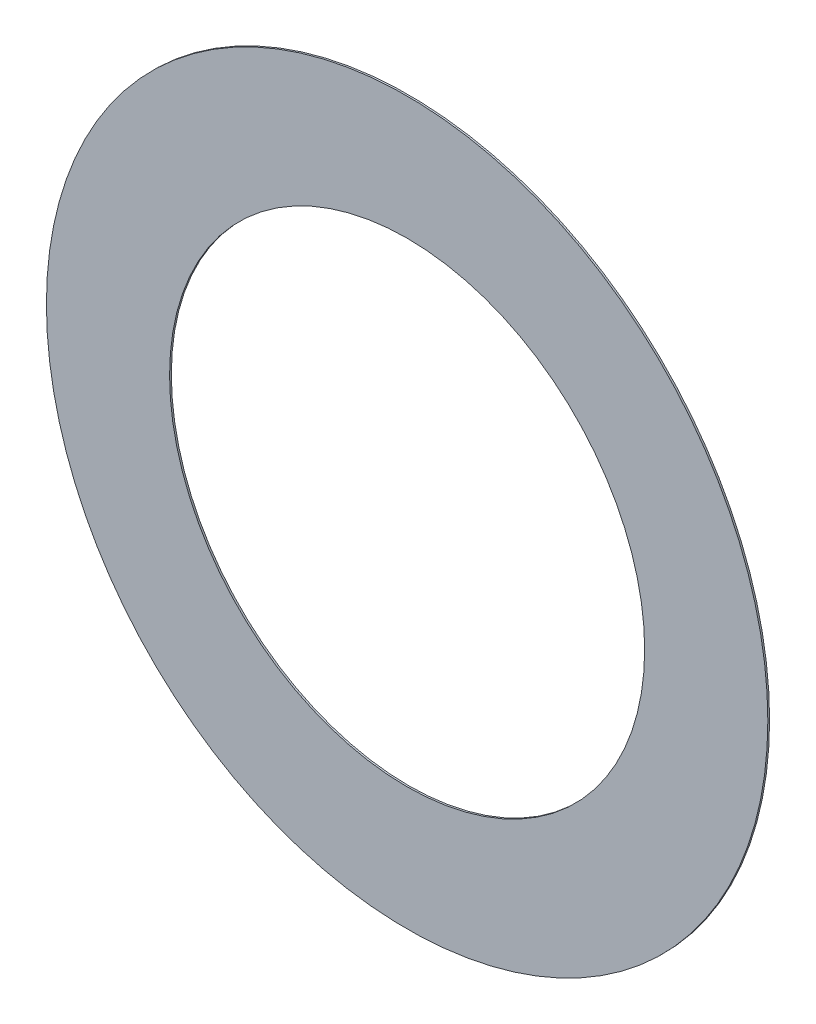
SolidWorks part; units mm, degrees
ref_plane "Front Plane" through (0, 0, 0) normal (0, 0, 1) x (1, 0, 0)
ref_plane "Top Plane" through (0, 0, 0) normal (0, 1, 0) x (1, 0, 0)
ref_plane "Right Plane" through (0, 0, 0) normal (1, 0, 0) x (0, 0, -1)
sketch "Sketch1" plane through (0, 0, 0) normal (0, 0, 1) x (1, 0, 0)
  circle A0 centre (0, 0) radius 20.5
  circle A1 centre (0, 0) radius 13.5
  dimension "D1" = 41
  dimension "D2" = 7
extrude "Boss-Extrude1" add sketch "Sketch1" along normal blind 0.1
